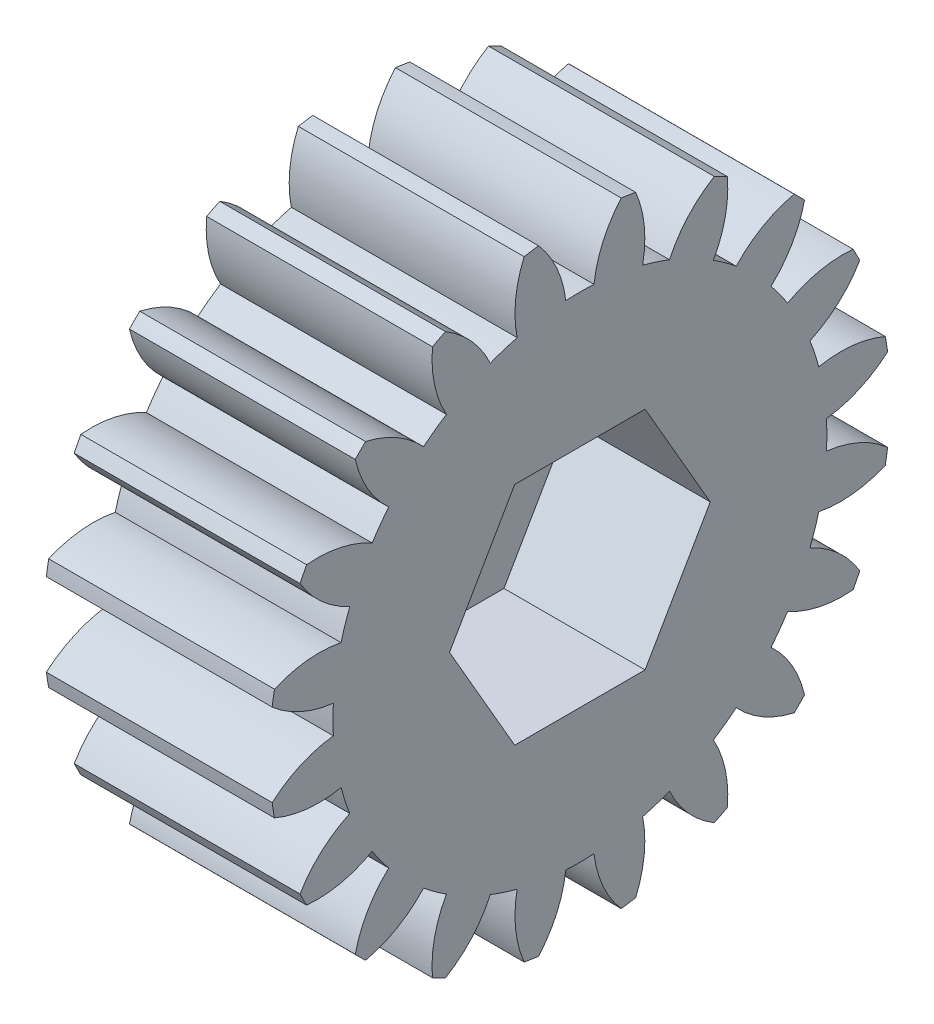
SolidWorks part; units mm, degrees
ref_plane "前基準面" through (0, 0, 0) normal (0, 0, 1) x (1, 0, 0)
ref_plane "上基準面" through (0, 0, 0) normal (0, 1, 0) x (1, 0, 0)
ref_plane "右基準面" through (0, 0, 0) normal (1, 0, 0) x (0, 0, -1)
ref_plane "平面1" through (0, 0, 0) normal (0, 0, -1) x (-1, 0, 0)
sketch "草圖1" plane through (0, 0, 0) normal (0, 0, -1) x (-1, 0, 0)
  line L0 (-8, 11) -> (-8, 0)
  line L1 (-8, 0) -> (0, 0)
  line L2 (0, 0) -> (0, 11)
  line L3 (0, 11) -> (-8, 11)
  line L4 (-8, 0) -> (0, 0) construction
revolve "旋轉1" add sketch "草圖1" angle 360 about L4
sketch "草圖2" plane through (0, 0, 0) normal (-1, 0, 0) x (0, 0, 1)
  arc A0 (10.902, -1.465) -> (10.902, 1.465) centre (0, 0) ccw
  arc A1 (10.902, 1.465) -> (8.7347, 0.4999) centre (8.2645, 4.4722) cw
  arc A2 (8.7347, 0.4999) -> (8.7347, -0.4999) centre (0, 0) cw
  arc A3 (8.7347, -0.4999) -> (10.902, -1.465) centre (8.2645, -4.4722) cw
extrude "除料-伸長1" cut sketch "草圖2" against normal through all
sketch "草圖3" plane through (0, 0, 0) normal (-1, 0, 0) x (0, 0, 1)
  arc A0 (9.9157, -4.7622) -> (10.8211, -1.9757) centre (0, 0) ccw
  arc A1 (10.8211, -1.9757) -> (8.4617, -2.2237) centre (9.242, 1.6994) cw
  arc A2 (8.4617, -2.2237) -> (8.1527, -3.1746) centre (0, 0) cw
  arc A3 (8.1527, -3.1746) -> (9.9157, -4.7622) centre (6.478, -6.8072) cw
extrude "除料-伸長2" cut sketch "草圖3" against normal through all
sketch "草圖4" plane through (0, 0, 0) normal (-1, 0, 0) x (0, 0, 1)
  arc A0 (7.9588, -7.5932) -> (9.681, -5.2229) centre (0, 0) ccw
  arc A1 (9.681, -5.2229) -> (7.3604, -4.7297) centre (9.3148, -1.2397) cw
  arc A2 (7.3604, -4.7297) -> (6.7727, -5.5386) centre (0, 0) cw
  arc A3 (6.7727, -5.5386) -> (7.9588, -7.5932) centre (4.0574, -8.4758) cw
extrude "除料-伸長3" cut sketch "草圖4" against normal through all
sketch "草圖5" plane through (0, 0, 0) normal (-1, 0, 0) x (0, 0, 1)
  arc A0 (5.2229, -9.681) -> (7.5932, -7.9588) centre (0, 0) ccw
  arc A1 (7.5932, -7.9588) -> (5.5386, -6.7727) centre (8.4758, -4.0574) cw
  arc A2 (5.5386, -6.7727) -> (4.7297, -7.3604) centre (0, 0) cw
  arc A3 (4.7297, -7.3604) -> (5.2229, -9.681) centre (1.2397, -9.3148) cw
extrude "除料-伸長4" cut sketch "草圖5" against normal through all
sketch "草圖6" plane through (0, 0, 0) normal (-1, 0, 0) x (0, 0, 1)
  arc A0 (1.9757, -10.8211) -> (4.7622, -9.9157) centre (0, 0) ccw
  arc A1 (4.7622, -9.9157) -> (3.1746, -8.1527) centre (6.8072, -6.478) cw
  arc A2 (3.1746, -8.1527) -> (2.2237, -8.4617) centre (0, 0) cw
  arc A3 (2.2237, -8.4617) -> (1.9757, -10.8211) centre (-1.6994, -9.242) cw
extrude "除料-伸長5" cut sketch "草圖6" against normal through all
sketch "草圖7" plane through (0, 0, 0) normal (-1, 0, 0) x (0, 0, 1)
  arc A0 (-1.465, -10.902) -> (1.465, -10.902) centre (0, 0) ccw
  arc A1 (1.465, -10.902) -> (0.4999, -8.7347) centre (4.4722, -8.2645) cw
  arc A2 (0.4999, -8.7347) -> (-0.4999, -8.7347) centre (0, 0) cw
  arc A3 (-0.4999, -8.7347) -> (-1.465, -10.902) centre (-4.4722, -8.2645) cw
extrude "除料-伸長6" cut sketch "草圖7" against normal through all
sketch "草圖8" plane through (0, 0, 0) normal (-1, 0, 0) x (0, 0, 1)
  arc A0 (-4.7622, -9.9157) -> (-1.9757, -10.8211) centre (0, 0) ccw
  arc A1 (-1.9757, -10.8211) -> (-2.2237, -8.4617) centre (1.6994, -9.242) cw
  arc A2 (-2.2237, -8.4617) -> (-3.1746, -8.1527) centre (0, 0) cw
  arc A3 (-3.1746, -8.1527) -> (-4.7622, -9.9157) centre (-6.8072, -6.478) cw
extrude "除料-伸長7" cut sketch "草圖8" against normal through all
sketch "草圖9" plane through (0, 0, 0) normal (-1, 0, 0) x (0, 0, 1)
  arc A0 (-7.5932, -7.9588) -> (-5.2229, -9.681) centre (0, 0) ccw
  arc A1 (-5.2229, -9.681) -> (-4.7297, -7.3604) centre (-1.2397, -9.3148) cw
  arc A2 (-4.7297, -7.3604) -> (-5.5386, -6.7727) centre (0, 0) cw
  arc A3 (-5.5386, -6.7727) -> (-7.5932, -7.9588) centre (-8.4758, -4.0574) cw
extrude "除料-伸長8" cut sketch "草圖9" against normal through all
sketch "草圖10" plane through (0, 0, 0) normal (-1, 0, 0) x (0, 0, 1)
  arc A0 (-9.681, -5.2229) -> (-7.9588, -7.5932) centre (0, 0) ccw
  arc A1 (-7.9588, -7.5932) -> (-6.7727, -5.5386) centre (-4.0574, -8.4758) cw
  arc A2 (-6.7727, -5.5386) -> (-7.3604, -4.7297) centre (0, 0) cw
  arc A3 (-7.3604, -4.7297) -> (-9.681, -5.2229) centre (-9.3148, -1.2397) cw
extrude "除料-伸長9" cut sketch "草圖10" against normal through all
sketch "草圖11" plane through (0, 0, 0) normal (-1, 0, 0) x (0, 0, 1)
  arc A0 (-10.8211, -1.9757) -> (-9.9157, -4.7622) centre (0, 0) ccw
  arc A1 (-9.9157, -4.7622) -> (-8.1527, -3.1746) centre (-6.478, -6.8072) cw
  arc A2 (-8.1527, -3.1746) -> (-8.4617, -2.2237) centre (0, 0) cw
  arc A3 (-8.4617, -2.2237) -> (-10.8211, -1.9757) centre (-9.242, 1.6994) cw
extrude "除料-伸長10" cut sketch "草圖11" against normal through all
sketch "草圖12" plane through (0, 0, 0) normal (-1, 0, 0) x (0, 0, 1)
  arc A0 (-10.902, 1.465) -> (-10.902, -1.465) centre (0, 0) ccw
  arc A1 (-10.902, -1.465) -> (-8.7347, -0.4999) centre (-8.2645, -4.4722) cw
  arc A2 (-8.7347, -0.4999) -> (-8.7347, 0.4999) centre (0, 0) cw
  arc A3 (-8.7347, 0.4999) -> (-10.902, 1.465) centre (-8.2645, 4.4722) cw
extrude "除料-伸長11" cut sketch "草圖12" against normal through all
sketch "草圖13" plane through (0, 0, 0) normal (-1, 0, 0) x (0, 0, 1)
  arc A0 (-9.9157, 4.7622) -> (-10.8211, 1.9757) centre (0, 0) ccw
  arc A1 (-10.8211, 1.9757) -> (-8.4617, 2.2237) centre (-9.242, -1.6994) cw
  arc A2 (-8.4617, 2.2237) -> (-8.1527, 3.1746) centre (0, 0) cw
  arc A3 (-8.1527, 3.1746) -> (-9.9157, 4.7622) centre (-6.478, 6.8072) cw
extrude "除料-伸長12" cut sketch "草圖13" against normal through all
sketch "草圖14" plane through (0, 0, 0) normal (-1, 0, 0) x (0, 0, 1)
  arc A0 (-7.9588, 7.5932) -> (-9.681, 5.2229) centre (0, 0) ccw
  arc A1 (-9.681, 5.2229) -> (-7.3604, 4.7297) centre (-9.3148, 1.2397) cw
  arc A2 (-7.3604, 4.7297) -> (-6.7727, 5.5386) centre (0, 0) cw
  arc A3 (-6.7727, 5.5386) -> (-7.9588, 7.5932) centre (-4.0574, 8.4758) cw
extrude "除料-伸長13" cut sketch "草圖14" against normal through all
sketch "草圖15" plane through (0, 0, 0) normal (-1, 0, 0) x (0, 0, 1)
  arc A0 (-5.2229, 9.681) -> (-7.5932, 7.9588) centre (0, 0) ccw
  arc A1 (-7.5932, 7.9588) -> (-5.5386, 6.7727) centre (-8.4758, 4.0574) cw
  arc A2 (-5.5386, 6.7727) -> (-4.7297, 7.3604) centre (0, 0) cw
  arc A3 (-4.7297, 7.3604) -> (-5.2229, 9.681) centre (-1.2397, 9.3148) cw
extrude "除料-伸長14" cut sketch "草圖15" against normal through all
sketch "草圖16" plane through (0, 0, 0) normal (-1, 0, 0) x (0, 0, 1)
  arc A0 (-1.9757, 10.8211) -> (-4.7622, 9.9157) centre (0, 0) ccw
  arc A1 (-4.7622, 9.9157) -> (-3.1746, 8.1527) centre (-6.8072, 6.478) cw
  arc A2 (-3.1746, 8.1527) -> (-2.2237, 8.4617) centre (0, 0) cw
  arc A3 (-2.2237, 8.4617) -> (-1.9757, 10.8211) centre (1.6994, 9.242) cw
extrude "除料-伸長15" cut sketch "草圖16" against normal through all
sketch "草圖17" plane through (0, 0, 0) normal (-1, 0, 0) x (0, 0, 1)
  arc A0 (1.465, 10.902) -> (-1.465, 10.902) centre (0, 0) ccw
  arc A1 (-1.465, 10.902) -> (-0.4999, 8.7347) centre (-4.4722, 8.2645) cw
  arc A2 (-0.4999, 8.7347) -> (0.4999, 8.7347) centre (0, 0) cw
  arc A3 (0.4999, 8.7347) -> (1.465, 10.902) centre (4.4722, 8.2645) cw
extrude "除料-伸長16" cut sketch "草圖17" against normal through all
sketch "草圖18" plane through (0, 0, 0) normal (-1, 0, 0) x (0, 0, 1)
  arc A0 (4.7622, 9.9157) -> (1.9757, 10.8211) centre (0, 0) ccw
  arc A1 (1.9757, 10.8211) -> (2.2237, 8.4617) centre (-1.6994, 9.242) cw
  arc A2 (2.2237, 8.4617) -> (3.1746, 8.1527) centre (0, 0) cw
  arc A3 (3.1746, 8.1527) -> (4.7622, 9.9157) centre (6.8072, 6.478) cw
extrude "除料-伸長17" cut sketch "草圖18" against normal through all
sketch "草圖19" plane through (0, 0, 0) normal (-1, 0, 0) x (0, 0, 1)
  arc A0 (7.5932, 7.9588) -> (5.2229, 9.681) centre (0, 0) ccw
  arc A1 (5.2229, 9.681) -> (4.7297, 7.3604) centre (1.2397, 9.3148) cw
  arc A2 (4.7297, 7.3604) -> (5.5386, 6.7727) centre (0, 0) cw
  arc A3 (5.5386, 6.7727) -> (7.5932, 7.9588) centre (8.4758, 4.0574) cw
extrude "除料-伸長18" cut sketch "草圖19" against normal through all
sketch "草圖20" plane through (0, 0, 0) normal (-1, 0, 0) x (0, 0, 1)
  arc A0 (9.681, 5.2229) -> (7.9588, 7.5932) centre (0, 0) ccw
  arc A1 (7.9588, 7.5932) -> (6.7727, 5.5386) centre (4.0574, 8.4758) cw
  arc A2 (6.7727, 5.5386) -> (7.3604, 4.7297) centre (0, 0) cw
  arc A3 (7.3604, 4.7297) -> (9.681, 5.2229) centre (9.3148, 1.2397) cw
extrude "除料-伸長19" cut sketch "草圖20" against normal through all
sketch "草圖21" plane through (0, 0, 0) normal (-1, 0, 0) x (0, 0, 1)
  arc A0 (10.8211, 1.9757) -> (9.9157, 4.7622) centre (0, 0) ccw
  arc A1 (9.9157, 4.7622) -> (8.1527, 3.1746) centre (6.478, 6.8072) cw
  arc A2 (8.1527, 3.1746) -> (8.4617, 2.2237) centre (0, 0) cw
  arc A3 (8.4617, 2.2237) -> (10.8211, 1.9757) centre (9.242, -1.6994) cw
extrude "除料-伸長20" cut sketch "草圖21" against normal through all
sketch "草圖22" plane through (8, 0, 0) normal (1, 0, 0) x (0, 0, -1)
  line L0 (-4.6188, 0) -> (-2.3094, -4)
  line L1 (-2.3094, -4) -> (2.3094, -4)
  line L2 (2.3094, -4) -> (4.6188, 0)
  line L3 (4.6188, 0) -> (2.3094, 4)
  line L4 (2.3094, 4) -> (-2.3094, 4)
  line L5 (-2.3094, 4) -> (-4.6188, 0)
extrude "除料-伸長21" cut sketch "草圖22" against normal blind 5
hole_wizard "Ø5.0 (5) 直徑孔1" positions "草圖24" profile "草圖23" hole size "Ø5.0" standard "Ansi Metric"
sketch "草圖24" plane through (0, 0, 0) normal (-1, 0, 0) x (0, 0, 1)
  point P0 (0, 0)
sketch "草圖23" plane through (0, 0, 0) normal (0, 1, 0) x (0, 0, 1)
  line L0 (0, 0) -> (0, 8)
  line L1 (0, 8) -> (2.5, 8)
  line L2 (2.5, 8) -> (2.5, 0)
  line L5 (2.5, 0) -> (0, 0)
  line L11 (0, -6.35) -> (0, 107.95) construction
  dimension "貫穿孔直徑" = 5
  dimension "貫穿孔深度" = 8
